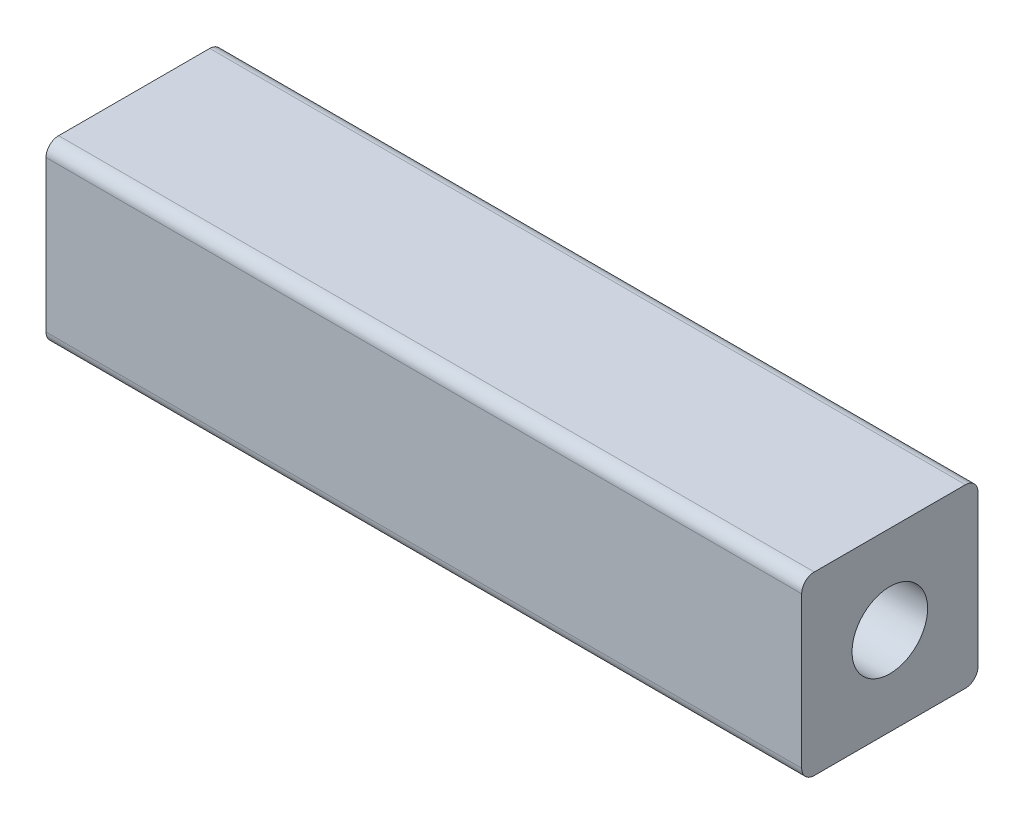
SolidWorks part; units mm, degrees
ref_plane "Front Plane" through (0, 0, 0) normal (0, 0, 1) x (1, 0, 0)
ref_plane "Top Plane" through (0, 0, 0) normal (0, 1, 0) x (1, 0, 0)
ref_plane "Right Plane" through (0, 0, 0) normal (1, 0, 0) x (0, 0, -1)
sketch "Sketch1" plane through (0, 0, 0) normal (1, 0, 0) x (0, 0, -1)
  line L1 (-7, 7) -> (7, 7)
  line L2 (-7, 7) -> (-7, -7)
  line L3 (-7, -7) -> (7, -7)
  line L4 (7, 7) -> (7, -7)
  line L5 (-7, 7) -> (7, -7) construction
  line L6 (-7, -7) -> (7, 7) construction
  point P0 (0, 0)
  point P1 (0, 0)
extrude "Boss-Extrude1" add sketch "Sketch1" along normal blind 60
fillet "Fillet1" radius 1 4 edges at (30, -7, -7) (30, -7, 7) (30, 7, 7) (30, 7, -7)
sketch "Sketch2" plane through (60, 0, 0) normal (1, 0, 0) x (0, 0, -1)
  circle A0 centre (0, 0) radius 3
extrude "Cut-Extrude1" cut sketch "Sketch2" against normal blind 44
